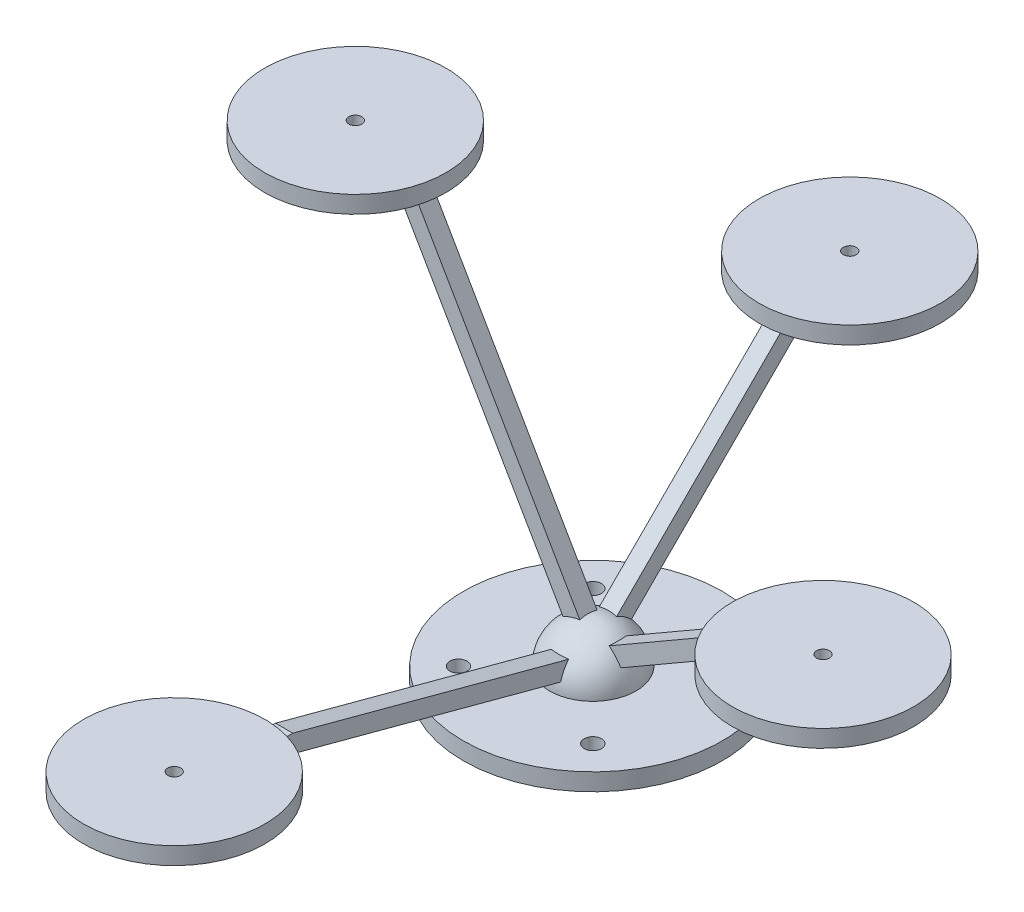
SolidWorks part; units mm, degrees
ref_plane "前视基准面" through (0, 0, 0) normal (0, 0, 1) x (1, 0, 0)
ref_plane "上视基准面" through (0, 0, 0) normal (0, 1, 0) x (1, 0, 0)
ref_plane "右视基准面" through (0, 0, 0) normal (1, 0, 0) x (0, 0, -1)
sketch "草图1" plane through (0, 0, 0) normal (0, 1, 0) x (1, 0, 0)
  line L0 (-23.4221, 0) -> (25.8766, 0) construction
  line L1 (0, 26.1921) -> (0, -25.0701) construction
  line L2 (-18.9498, 18.9498) -> (18.8862, -18.8862) construction
  line L3 (18.9424, 18.9424) -> (-20.2044, -20.2044) construction
  circle A0 centre (0, 0) radius 15
  circle A1 centre (0, 0) radius 11 construction
  circle A2 centre (7.7782, 7.7782) radius 1
  circle A3 centre (-7.7782, 7.7782) radius 1
  circle A4 centre (-7.7782, -7.7782) radius 1
  circle A5 centre (7.7782, -7.7782) radius 1
  dimension "D1" = 30
  dimension "D4" = 22
  dimension "D5" = 2
  dimension "D2" = 45
  dimension "D3" = 45
extrude "凸台-拉伸1" add sketch "草图1" along normal blind 2
sketch "草图2" plane through (0, 0, 0) normal (1, 0, 0) x (0, 0, -1)
  line L0 (0, 2) -> (0, 7)
  line L1 (15, 2) -> (-15, 2) construction
  line L2 (0, 2) -> (5, 2)
  arc A0 (0, 7) -> (5, 2) centre (0, 2) cw
  dimension "D1" = 5
revolve "旋转1" add sketch "草图2" angle 360 about L0
sketch "草图3" plane through (0, 0, 0) normal (0, 0, 1) x (1, 0, 0)
  line L0 (0, 2) -> (0, 9.7216) construction
  line L1 (15, 2) -> (-15, 2) construction
  line L2 (0, 2) -> (21.6506, 14.5)
  line L3 (8.7782, 2) -> (6.7782, 2) construction
  line L4 (0, 4.3094) -> (17.6506, 14.5)
  line L6 (17.6506, 14.5) -> (21.6506, 14.5)
  line L7 (0, 2) -> (-22.5, 40.9711)
  line L8 (-20.1906, 40.9711) -> (0, 6)
  line L9 (0, 6) -> (0, 4.3094)
  line L10 (-22.5, 40.9711) -> (-20.1906, 40.9711)
  dimension "D1" = 30
  dimension "D2" = 25
  dimension "D3" = 2
  dimension "D4" = 60
  dimension "D5" = 45
  dimension "D6" = 2
extrude "凸台-拉伸2" add sketch "草图3" along normal mid plane 2
sketch "草图4" plane through (0, 14.5, 0) normal (0, 1, 0) x (1, 0, 0)
  line L0 (21.6506, -1) -> (21.6506, 1) construction
  circle A0 centre (26.6506, 0) radius 10.5
  circle A1 centre (26.6506, 0) radius 0.75
  dimension "D1" = 21
  dimension "D2" = 1.5
  dimension "D3" = 5
extrude "凸台-拉伸3" add sketch "草图4" along normal blind 2
sketch "草图5" plane through (0, 40.9711, 0) normal (0, 1, 0) x (1, 0, 0)
  line L0 (-22.5, -1) -> (-22.5, 1) construction
  circle A0 centre (-27.5, 0) radius 10.5
  circle A1 centre (-27.5, 0) radius 0.75
  dimension "D1" = 21
  dimension "D2" = 1.5
  dimension "D3" = 5
extrude "凸台-拉伸4" add sketch "草图5" along normal blind 2
sketch "草图6" plane through (0, 0, 0) normal (1, 0, 0) x (0, 0, -1)
  line L0 (0, 0) -> (0, 10.6928) construction
  line L1 (0, 2) -> (24.7487, 26.7487)
  line L2 (15, 2) -> (-15, 2) construction
  line L3 (8.7782, 2) -> (6.7782, 2) construction
  line L4 (0, 4.8284) -> (21.9203, 26.7487)
  line L5 (21.9203, 26.7487) -> (24.7487, 26.7487)
  line L6 (0, 2) -> (-43.4667, 13.6469)
  line L7 (0, 4.0706) -> (-35.7393, 13.6469)
  line L8 (-43.4667, 13.6469) -> (-35.7393, 13.6469)
  line L9 (0, 4.0706) -> (0, 4.8284)
  dimension "D1" = 45
  dimension "D2" = 35
  dimension "D3" = 2
  dimension "D4" = 15
  dimension "D5" = 45
  dimension "D6" = 2
extrude "凸台-拉伸5" add sketch "草图6" along normal mid plane 2
sketch "草图7" plane through (0, 26.7487, 0) normal (0, 1, 0) x (1, 0, 0)
  line L0 (1, 24.7487) -> (-1, 24.7487) construction
  circle A0 centre (0, 29.7487) radius 10.5
  circle A1 centre (0, 29.7487) radius 0.75
  dimension "D1" = 21
  dimension "D2" = 1.5
  dimension "D3" = 5
extrude "凸台-拉伸6" add sketch "草图7" along normal blind 2
sketch "草图8" plane through (0, 13.6469, 0) normal (0, 1, 0) x (1, 0, 0)
  line L0 (1, -43.4667) -> (-1, -43.4667) construction
  circle A0 centre (0, -48.4667) radius 10.5
  circle A1 centre (0, -48.4667) radius 0.75
  dimension "D1" = 1.5
  dimension "D2" = 21
  dimension "D3" = 5
extrude "凸台-拉伸7" add sketch "草图8" along normal blind 2
